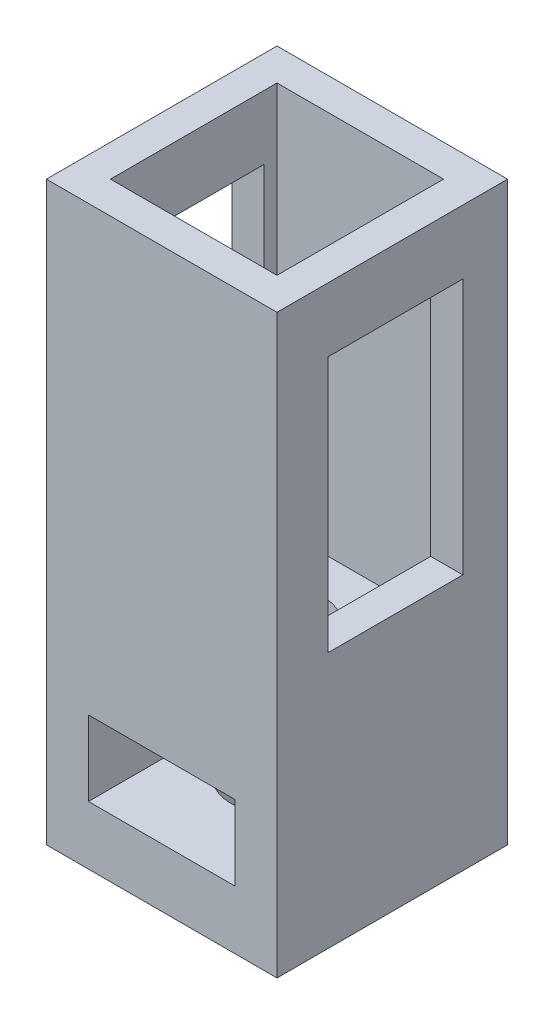
SolidWorks part; units mm, degrees
ref_plane "Front Plane" through (0, 0, 0) normal (0, 0, 1) x (1, 0, 0)
ref_plane "Top Plane" through (0, 0, 0) normal (0, 1, 0) x (1, 0, 0)
ref_plane "Right Plane" through (0, 0, 0) normal (1, 0, 0) x (0, 0, -1)
sketch "Sketch1" plane through (0, 0, 0) normal (0, 1, 0) x (1, 0, 0)
  line L1 (0, 0) -> (18, 0)
  line L2 (0, 0) -> (0, 18)
  line L3 (0, 18) -> (18, 18)
  line L4 (18, 0) -> (18, 18)
  dimension "D1" = 18
  dimension "D2" = 18
extrude "Boss-Extrude1" add sketch "Sketch1" along normal blind 35
sketch "Sketch5" plane through (0, 35, 0) normal (0, 1, 0) x (1, 0, 0)
  line L0 (-9.9, 0) -> (9.9, 0) construction
  line L1 (2.5, 15.5) -> (15.5, 15.5)
  line L2 (2.5, 15.5) -> (2.5, 2.5)
  line L3 (2.5, 2.5) -> (15.5, 2.5)
  line L4 (15.5, 15.5) -> (15.5, 2.5)
  line L5 (18, 18) -> (0, 18) construction
  line L6 (18, 0) -> (18, 18) construction
  dimension "D1" = 13
  dimension "D2" = 13
  dimension "D3" = 2.5
  dimension "D4" = 2.5
  dimension "D5" = 2.5
  dimension "D6" = 2.5
extrude "Cut-Extrude1" cut sketch "Sketch5" against normal blind 30
sketch "Sketch7" plane through (18, 0, 0) normal (1, 0, 0) x (0, 0, -1)
  line L0 (0, 35) -> (18, 35) construction
  line L1 (4, 30) -> (14.5, 30)
  line L2 (4, 30) -> (4, 10)
  line L3 (4, 10) -> (14.5, 10)
  line L4 (14.5, 30) -> (14.5, 10)
  line L5 (18, 35) -> (18, 0) construction
  line L6 (0, 9.9) -> (0, -9.9) construction
  dimension "D1" = 20
  dimension "D2" = 5
  dimension "D3" = 10.5
  dimension "D4" = 3.5
  dimension "D5" = 4
extrude "Cut-Extrude3" cut sketch "Sketch7" against normal through all
sketch "Sketch8" plane through (0, 0, 0) normal (0, -1, 0) x (1, 0, 0)
  line L1 (0, 0) -> (18, 0)
  line L2 (0, 0) -> (0, -18)
  line L3 (0, -18) -> (18, -18)
  line L4 (18, 0) -> (18, -18)
extrude "Boss-Extrude2" add sketch "Sketch8" along normal blind 10
sketch "Sketch9" plane through (0, 0, 0) normal (0, 0, 1) x (1, 0, 0)
  line L0 (18, 35) -> (18, -10) construction
  line L1 (3.285, 0.425) -> (14.715, 0.425)
  line L2 (3.285, 0.425) -> (3.285, -5.425)
  line L3 (3.285, -5.425) -> (14.715, -5.425)
  line L4 (14.715, 0.425) -> (14.715, -5.425)
  line L5 (0, 35) -> (0, -10) construction
  line L6 (18, -10) -> (0, -10) construction
  line L7 (2.5, 5) -> (15.5, 5) construction
  dimension "D1" = 5.85
  dimension "D2" = 11.43
  dimension "D3" = 3.285
  dimension "D4" = 3.285
  dimension "D5" = 4.575
  dimension "D6" = 4.575
extrude "Cut-Extrude4" cut sketch "Sketch9" against normal through all
hole_wizard "1/4 Clearance Hole1" positions "Sketch11" profile "Sketch10" hole size "1/4" standard "ANSI Inch"
sketch "Sketch11" plane through (0, -10, 0) normal (0, -1, 0) x (-1, 0, 0)
  line L0 (-18, 0) -> (0, 0) construction
  line L1 (0, 18) -> (-18, 18) construction
  line L2 (-18, 18) -> (-18, 0) construction
  point P0 (-9, 9)
  dimension "D1" = 9
  dimension "D2" = 9
  dimension "D3" = 9
sketch "Sketch10" plane through (9, -10, -9) normal (1, 0, 0) x (0, 0, -1)
  line L0 (0, 0) -> (0, 17.1458)
  line L1 (0, 17.1458) -> (3.5712, 15)
  line L2 (3.5712, 15) -> (3.5712, 0)
  line L5 (3.5712, 0) -> (0, 0)
  line L10 (0, 17.1458) -> (-3.5712, 15) construction
  line L11 (0, -6.35) -> (0, 107.95) construction
  dimension "Hole Dia." = 7.1425
  dimension "Hole Depth" = 15
  dimension "Drill Angle" = 118
